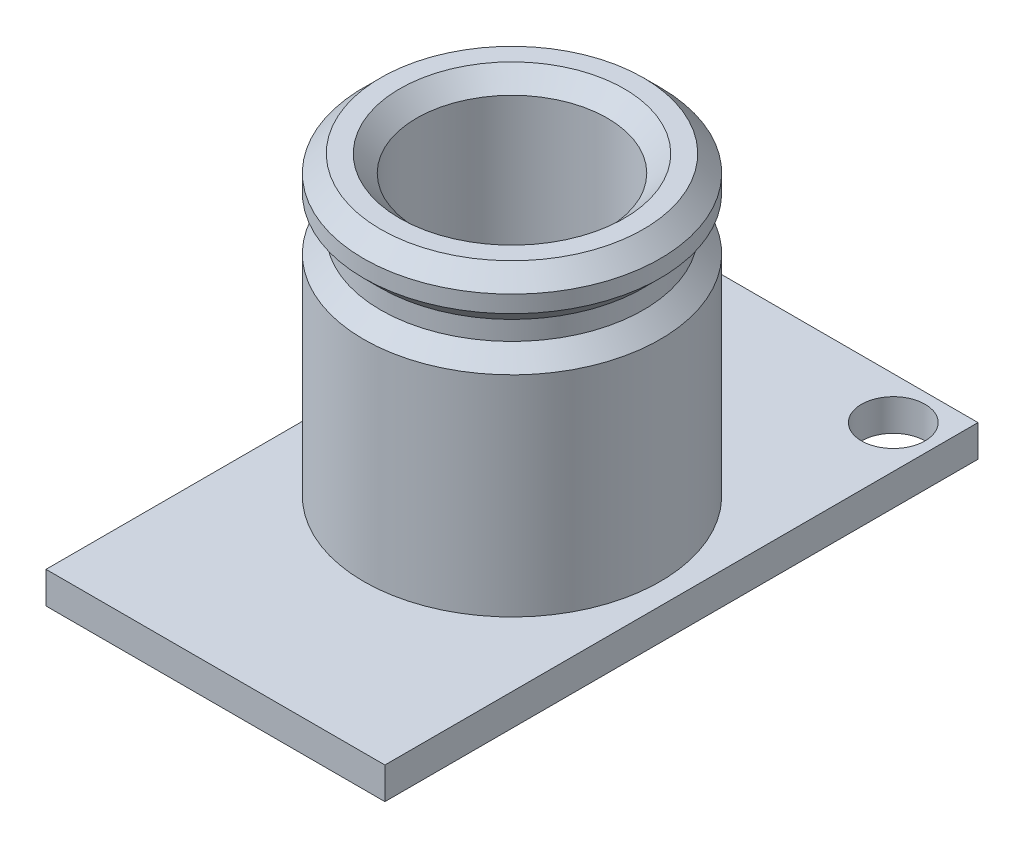
SolidWorks part; units mm, degrees
material "ABS"
ref_plane "Front Plane" through (0, 0, 0) normal (0, 0, 1) x (1, 0, 0)
ref_plane "Top Plane" through (0, 0, 0) normal (0, 1, 0) x (1, 0, 0)
ref_plane "Right Plane" through (0, 0, 0) normal (1, 0, 0) x (0, 0, -1)
sketch "Sketch1" plane through (0, 0, 0) normal (0, 1, 0) x (1, 0, 0)
  line L1 (-8, 14) -> (8, 14)
  line L2 (-8, 14) -> (-8, -14)
  line L3 (-8, -14) -> (8, -14)
  line L4 (8, 14) -> (8, -14)
  line L5 (0, -14) -> (0, 14) construction
  line L6 (-8, 0) -> (8, 0) construction
  point P0 (0, 0)
  dimension "D1" = 16
  dimension "D2" = 28
extrude "Boss-Extrude1" add sketch "Sketch1" along normal blind 1.5
sketch "Sketch5" plane through (0, 1.5, 0) normal (0, 1, 0) x (1, 0, 0)
  line L0 (-8, 14) -> (8, 14) construction
  line L1 (-8, 14) -> (-8, -14) construction
  circle A0 centre (-6, 12) radius 1.5
  dimension "D1" = 3
  dimension "D2" = 2
  dimension "D3" = 2
extrude "Cut-Extrude2" cut sketch "Sketch5" against normal through all
mirror "Mirror1" about plane through (0, 0, 0) normal (1, 0, 0) of "Cut-Extrude2"
sketch "Sketch2" plane through (0, 1.5, 0) normal (0, 1, 0) x (1, 0, 0)
  line L0 (0, -14) -> (0, 14) construction
  line L1 (-8, 0) -> (8, 0) construction
  circle A0 centre (0, 0) radius 7
  dimension "D1" = 14
extrude "Boss-Extrude2" add sketch "Sketch2" along normal blind 14 separate body
chamfer "Chamfer1" distance 0.8 angle 45 1 edges at (0, 15.5, 7)
sketch "Sketch3" plane through (0, 0, 0) normal (1, 0, 0) x (0, 0, -1)
  line L0 (7, 13.9) -> (6.2, 13.1)
  line L1 (7, 1.5) -> (7, 14.7) construction
  line L2 (6.2, 13.1) -> (6.2, 12.2)
  line L3 (6.2, 12.2) -> (7, 11.4)
  line L4 (7, 11.4) -> (7, 13.9)
  line L5 (-7, 14.7) -> (7, 14.7) construction
  line L6 (0, -1000) -> (0, 49000) construction
  dimension "D1" = 45
  dimension "D2" = 0.8
  dimension "D3" = 0.8
  dimension "D4" = 2.5
revolve "Cut-Revolve1" cut sketch "Sketch3" angle 360 about L6
sketch "Sketch4" plane through (0, 15.5, 0) normal (0, 1, 0) x (1, 0, 0)
  circle A0 centre (0, 0) radius 4.5
  dimension "D1" = 9
extrude "Cut-Extrude1" cut sketch "Sketch4" against normal blind 8
chamfer "Chamfer2" distance 0.8 angle 45 1 edges at (0, 15.5, 4.5)
